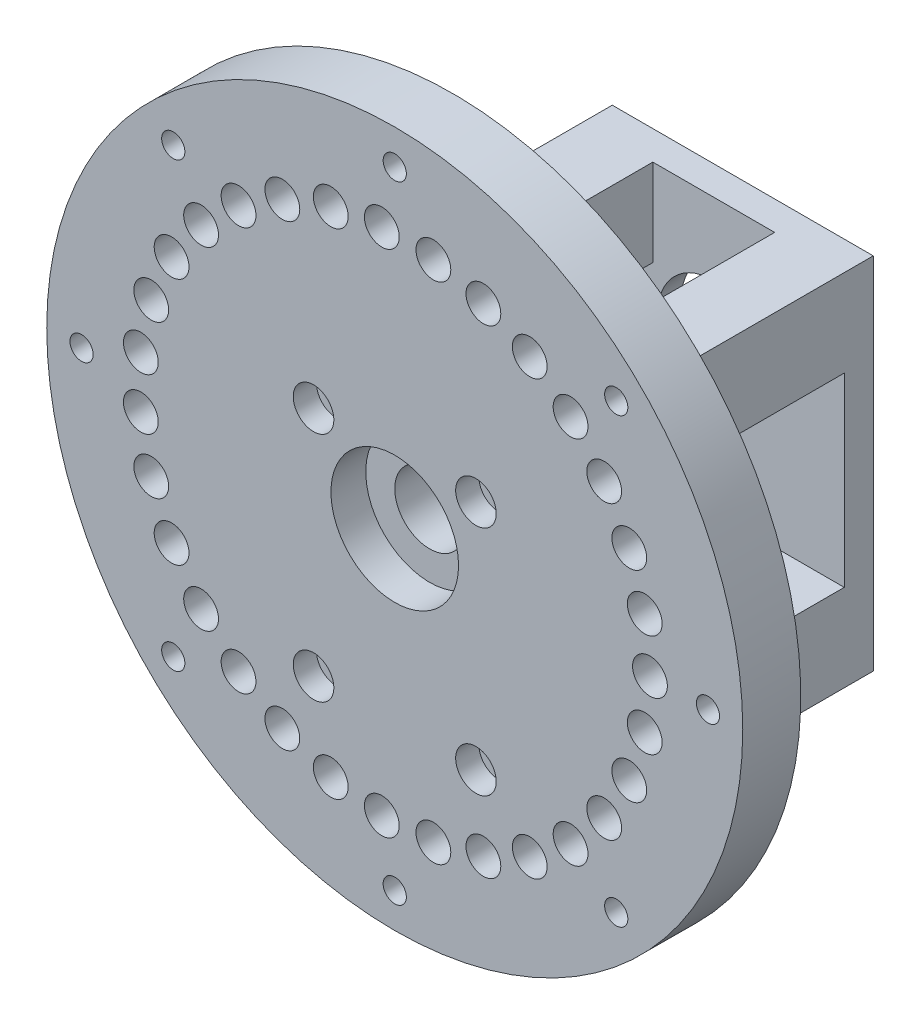
SolidWorks part; units mm, degrees
ref_plane "Front Plane" through (0, 0, 0) normal (0, 0, 1) x (1, 0, 0)
ref_plane "Top Plane" through (0, 0, 0) normal (0, 1, 0) x (1, 0, 0)
ref_plane "Right Plane" through (0, 0, 0) normal (1, 0, 0) x (0, 0, -1)
sketch "Sketch1" plane through (0, 0, 0) normal (0, 0, 1) x (1, 0, 0)
  line L0 (0, 0) -> (0, 60) construction
  line L1 (-2.2286, 43.9435) -> (0, 0) construction
  line L2 (0, 0) -> (44, 0) construction
  circle A0 centre (44, 0) radius 3
  circle A1 centre (43.0993, -8.8571) radius 3
  circle A2 centre (40.4341, -17.3517) radius 3
  circle A3 centre (36.1136, -25.1358) radius 3
  circle A4 centre (30.3145, -31.8909) radius 3
  circle A5 centre (23.2744, -37.3403) radius 3
  circle A6 centre (15.2814, -41.2611) radius 3
  circle A7 centre (6.6628, -43.4926) radius 3
  circle A8 centre (-2.2286, -43.9435) radius 3
  circle A9 centre (-11.0287, -42.5954) radius 3
  circle A10 centre (-19.3773, -39.5034) radius 3
  circle A11 centre (-26.9327, -34.7941) radius 3
  circle A12 centre (-33.3854, -28.6604) radius 3
  circle A13 centre (-38.4713, -21.3533) radius 3
  circle A14 centre (-41.9821, -13.172) radius 3
  circle A15 centre (-43.7743, -4.4514) radius 3
  circle A16 centre (-43.7743, 4.4514) radius 3
  circle A17 centre (-41.9821, 13.172) radius 3
  circle A18 centre (-38.4713, 21.3533) radius 3
  circle A19 centre (-33.3854, 28.6604) radius 3
  circle A20 centre (-26.9327, 34.7941) radius 3
  circle A21 centre (-19.3773, 39.5034) radius 3
  circle A22 centre (-11.0287, 42.5954) radius 3
  circle A23 centre (-2.2286, 43.9435) radius 3
  circle A24 centre (6.6628, 43.4926) radius 3
  circle A25 centre (15.2814, 41.2611) radius 3
  circle A26 centre (23.2744, 37.3403) radius 3
  circle A27 centre (30.3145, 31.8909) radius 3
  circle A28 centre (36.1136, 25.1358) radius 3
  circle A29 centre (40.4341, 17.3517) radius 3
  circle A30 centre (43.0993, 8.8571) radius 3
  arc A31 (59.9668, 1.9948) -> (59.9668, -1.9948) centre (0, 0) ccw
  circle A32 centre (0, 0) radius 11
  arc A33 (59.9668, -1.9948) -> (59.9668, 1.9948) centre (60, 0) ccw
  point P65 (0, 0)
  point P81 (0, 0)
  dimension "D1" = 6
  dimension "D4" = 120
  dimension "D5" = 22
  dimension "D2" = 44
  dimension "D3" = 31
extrude "Boss-Extrude1" add sketch "Sketch1" along normal blind 5
sketch "Sketch2" plane through (0, 0, 0) normal (0, 0, -1) x (-1, 0, 0)
  circle A0 centre (0, 0) radius 60
  circle A1 centre (0, 0) radius 6
  dimension "D1" = 12
extrude "Boss-Extrude2" add sketch "Sketch2" along normal blind 5
sketch "Sketch3" plane through (0, 0, 5) normal (0, 0, 1) x (1, 0, 0)
  line L0 (0, 0) -> (54, 0) construction
  circle A0 centre (0, 54) radius 2
  circle A1 centre (38.1838, 38.1838) radius 2
  circle A2 centre (54, 0) radius 2
  circle A3 centre (38.1838, -38.1838) radius 2
  circle A4 centre (0, -54) radius 2
  circle A5 centre (-38.1838, -38.1838) radius 2
  circle A6 centre (-54, 0) radius 2
  circle A7 centre (-38.1838, 38.1838) radius 2
  point P12 (0, 0)
  dimension "D1" = 4
  dimension "D2" = 54
  dimension "D3" = 8
extrude "Cut-Extrude1" cut sketch "Sketch3" against normal blind 35
sketch "Sketch4" plane through (0, 0, 0) normal (0, 0, 1) x (1, 0, 0)
  circle A0 centre (0, 0) radius 11
extrude "Cut-Extrude2" cut sketch "Sketch4" against normal blind 1
sketch "Sketch5" plane through (0, 0, -5) normal (0, 0, -1) x (-1, 0, 0)
  circle A0 centre (-14, 11) radius 2
  circle A1 centre (14, 11) radius 2
  circle A2 centre (14, -29) radius 2
  circle A3 centre (-14, -29) radius 2
  point P0 (0, 0)
  dimension "D4" = 4
  dimension "D2" = 28
  dimension "D3" = 40
extrude "Cut-Extrude3" cut sketch "Sketch5" against normal through all both and the other way through all
sketch "Sketch6" plane through (0, 0, -5) normal (0, 0, -1) x (-1, 0, 0)
  line L0 (-14, 11) -> (-14, -29) construction
  line L1 (-14, -9) -> (0, -9) construction
  line L2 (-22.5, 22) -> (22.5, 22)
  line L3 (-22.5, 22) -> (-22.5, -40)
  line L4 (-22.5, -40) -> (22.5, -40)
  line L5 (22.5, 22) -> (22.5, -40)
  line L6 (-22.5, 22) -> (22.5, -40) construction
  line L7 (-22.5, -40) -> (22.5, 22) construction
  point P4 (0, -9)
  dimension "D1" = 62
  dimension "D2" = 45
extrude "Boss-Extrude3" add sketch "Sketch6" along normal blind 50
sketch "Sketch7" plane through (0, 0, 5) normal (0, 0, 1) x (1, 0, 0)
  circle A0 centre (-14, 11) radius 2
  circle A1 centre (14, 11) radius 2
  circle A2 centre (14, -29) radius 2
  circle A3 centre (-14, -29) radius 2
  circle A4 centre (0, 0) radius 6
extrude "Cut-Extrude4" cut sketch "Sketch7" against normal blind 40
sketch "Sketch8" plane through (0, 0, -55) normal (0, 0, -1) x (-1, 0, 0)
  circle A0 centre (0, 0) radius 9.6
  dimension "D1" = 19.2
extrude "Cut-Extrude5" cut sketch "Sketch8" against normal blind 5 and the other way blind 88
sketch "Sketch9" plane through (-22.5, 0, 0) normal (-1, 0, 0) x (0, 0, 1)
  line L0 (-55, -9) -> (-5, -9) construction
  line L1 (-10, -25) -> (-50, -25)
  line L2 (-10, -25) -> (-10, 7)
  line L3 (-10, 7) -> (-50, 7)
  line L4 (-50, -25) -> (-50, 7)
  line L5 (-10, -25) -> (-50, 7) construction
  line L6 (-10, 7) -> (-50, -25) construction
  line L7 (-55, -40) -> (-55, 22) construction
  line L8 (-5, -40) -> (-5, 22) construction
  line L9 (-55, 22) -> (-5, 22) construction
  point P0 (-30, -9)
  point P11 (0, 0)
  dimension "D1" = 5
  dimension "D2" = 5
  dimension "D3" = 15
extrude "Cut-Extrude6" cut sketch "Sketch9" against normal blind 71
sketch "Sketch10" plane through (0, 0, 5) normal (0, 0, 1) x (1, 0, 0)
  circle A0 centre (-14, 11) radius 3.5
  circle A1 centre (14, 11) radius 3.5
  circle A2 centre (-14, -29) radius 3.5
  circle A3 centre (14, -29) radius 3.5
  dimension "D1" = 7
  dimension "D2" = 7
  dimension "D3" = 7
  dimension "D4" = 7
extrude "Cut-Extrude7" cut sketch "Sketch10" against normal blind 4
fillet "Fillet1" radius 4 4 edges at (-22.5, -9, -5) (0, -40, -5) (22.5, -9, -5) (0, 22, -5)
sketch "Sketch11" plane through (0, 0, -55) normal (0, 0, -1) x (-1, 0, 0)
  line L1 (-20, 20) -> (20, 20)
  line L2 (-20, 20) -> (-20, -38)
  line L3 (-20, -38) -> (20, -38)
  line L4 (20, 20) -> (20, -38)
  line L5 (-20, 20) -> (20, -38) construction
  line L6 (-20, -38) -> (20, 20) construction
  point P0 (0, -9)
  point P7 (-20, -9)
  dimension "D1" = 58
  dimension "D2" = 40
  dimension "D3" = 9
extrude "Cut-Extrude8" cut sketch "Sketch11" against normal blind 1
sketch "Sketch12" plane through (0, -40, 0) normal (0, -1, 0) x (1, 0, 0)
  line L0 (0, -9) -> (0, -55) construction
  line L1 (-10.5, -14) -> (10.5, -14)
  line L2 (-10.5, -14) -> (-10.5, -50)
  line L3 (-10.5, -50) -> (10.5, -50)
  line L4 (10.5, -14) -> (10.5, -50)
  line L5 (-10.5, -14) -> (10.5, -50) construction
  line L6 (-10.5, -50) -> (10.5, -14) construction
  line L7 (22.5, -9) -> (-22.5, -9) construction
  line L8 (22.5, -55) -> (-22.5, -55) construction
  line L9 (-22.5, -55) -> (-22.5, -9) construction
  point P0 (0, -32)
  point P11 (0, 0)
  dimension "D1" = 5
  dimension "D2" = 5
  dimension "D3" = 12
extrude "Cut-Extrude9" cut sketch "Sketch12" against normal blind 88
sketch "Sketch13" plane through (0, 0, 1) normal (0, 0, 1) x (1, 0, 0)
  circle A0 centre (-14, 11) radius 2
  circle A1 centre (14, 11) radius 2
  circle A2 centre (14, -29) radius 2
  circle A3 centre (-14, -29) radius 2
extrude "Cut-Extrude10" cut sketch "Sketch13" against normal blind 88
sketch "Sketch14" plane through (0, 0, 5) normal (0, 0, 1) x (1, 0, 0)
  circle A0 centre (0, 0) radius 82.6446
  circle A1 centre (0, 0) radius 60
extrude "Cut-Extrude11" cut sketch "Sketch14" against normal blind 10
sketch "Sketch15" plane through (0, 0, -54) normal (0, 0, -1) x (-1, 0, 0)
  line L0 (0, 20) -> (0, 0) construction
  line L1 (20, 20) -> (-20, 20) construction
  circle A0 centre (14, 11) radius 4.1
  circle A1 centre (-14, 11) radius 4.1
  circle A2 centre (-14, -29) radius 4.1
  circle A3 centre (14, -29) radius 4.1
  dimension "D1" = 8.2
  dimension "D2" = 8.2
  dimension "D3" = 8.2
  dimension "D4" = 8.2
extrude "Cut-Extrude12" cut sketch "Sketch15" against normal blind 2
